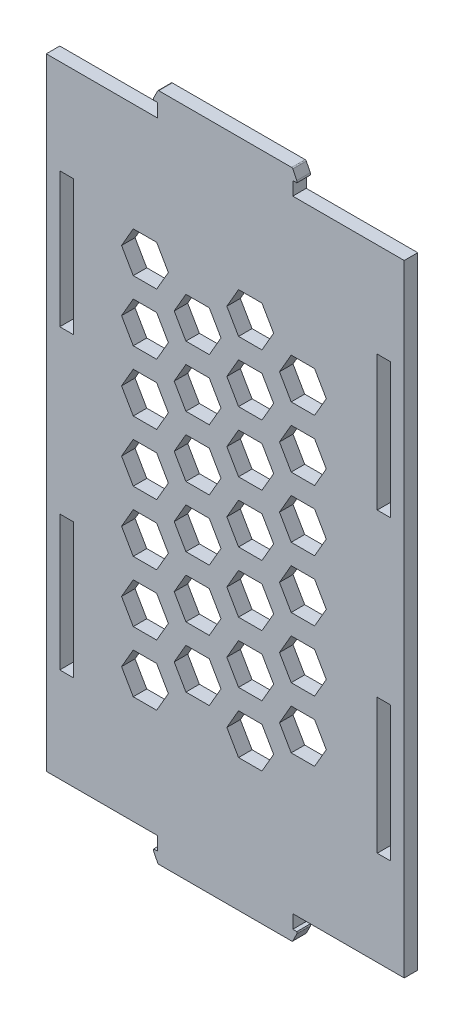
SolidWorks part; units mm, degrees
ref_plane "Front Plane" through (0, 0, 0) normal (0, 0, 1) x (1, 0, 0)
ref_plane "Top Plane" through (0, 0, 0) normal (0, 1, 0) x (1, 0, 0)
ref_plane "Right Plane" through (0, 0, 0) normal (1, 0, 0) x (0, 0, -1)
sketch "Sketch1" plane through (0, 0, 0) normal (0, 0, 1) x (1, 0, 0)
  line L0 (4, 0) -> (49, 0) construction
  line L1 (49, 0) -> (49, 92) construction
  line L2 (16.5, 0) -> (0, 0)
  line L3 (4, 92) -> (4, 0) construction
  line L8 (4, 46) -> (49, 46) construction
  line L30 (36.5, 0) -> (53, 0)
  line L44 (26.5, 68.0905) -> (26.5, 23.9095) construction
  line L45 (4, 78) -> (2, 78)
  line L46 (4, 78) -> (4, 58)
  line L47 (4, 58) -> (2, 58)
  line L48 (2, 78) -> (2, 58)
  line L49 (49, 78) -> (51, 78)
  line L50 (49, 78) -> (49, 58)
  line L51 (49, 58) -> (51, 58)
  line L52 (51, 78) -> (51, 58)
  line L69 (53, 0) -> (53, 92)
  line L77 (53, 92) -> (36.5, 92)
  line L99 (16.5, 92) -> (0, 92)
  line L100 (49, 14) -> (51, 14)
  line L101 (0, 92) -> (0, 0)
  line L102 (51, 14) -> (51, 34)
  line L103 (49, 34) -> (51, 34)
  line L104 (49, 14) -> (49, 34)
  line L105 (4, 14) -> (2, 14)
  line L106 (2, 14) -> (2, 34)
  line L107 (4, 34) -> (2, 34)
  line L108 (4, 14) -> (4, 34)
  line B0 (36.5, 0) -> (16.5, 0) construction
  line B1 (36.3382, -3.6) -> (16.6618, -3.6)
  line B2 (36.5, 0) -> (36.5, -2)
  line B3 (36.5, -3.5) -> (16.5, -3.5) construction
  line B4 (26.5, -3.5) -> (26.5, 0) construction
  line B5 (16.5, 0) -> (16.5, -2)
  line B6 (15.9, -2.3) -> (16.5, -3.5)
  line B7 (37.1, -2.3) -> (36.5, -3.5)
  line B8 (36.5, -2) -> (37.1, -2)
  line B9 (16.5, -2) -> (15.9, -2)
  arc B10 (36.5, -2) -> (37.1, -2.3) centre (36.8, -2.15) cw construction
  arc B11 (36.5, -3.5) -> (36.3382, -3.6) centre (36.3382, -3.4191) cw
  arc B12 (16.5, -3.5) -> (16.6618, -3.6) centre (16.6618, -3.4191) ccw
  arc B13 (37.1, -2) -> (37.1, -2.3) centre (36.8, -2.15) cw
  arc B14 (15.9, -2) -> (15.9, -2.3) centre (16.2, -2.15) ccw
  line B15 (36.5, 92) -> (16.5, 92) construction
  line B16 (36.3382, 95.6) -> (16.6618, 95.6)
  line B17 (36.5, 92) -> (36.5, 94)
  line B18 (36.5, 95.5) -> (16.5, 95.5) construction
  line B19 (26.5, 95.5) -> (26.5, 92) construction
  line B20 (16.5, 92) -> (16.5, 94)
  line B21 (15.9, 94.3) -> (16.5, 95.5)
  line B22 (37.1, 94.3) -> (36.5, 95.5)
  line B23 (36.5, 94) -> (37.1, 94)
  line B24 (16.5, 94) -> (15.9, 94)
  arc B25 (36.5, 94) -> (37.1, 94.3) centre (36.8, 94.15) ccw construction
  arc B26 (36.5, 95.5) -> (36.3382, 95.6) centre (36.3382, 95.4191) ccw
  arc B27 (16.5, 95.5) -> (16.6618, 95.6) centre (16.6618, 95.4191) cw
  arc B28 (37.1, 94) -> (37.1, 94.3) centre (36.8, 94.15) ccw
  arc B29 (15.9, 94) -> (15.9, 94.3) centre (16.2, 94.15) cw
  dimension "D3" = 12
  dimension "D4" = 2
  dimension "D16" = 92
  dimension "D17" = 20
  dimension "D18" = 2
  dimension "D20" = 22.5
sketch_block_instance "insert_bloquant_20mm-2mm-4"
sketch_block "insert_bloquant_20mm-2mm" parameters "D1"=2, "D2"=1.5, "D3"=1.2, "D4"=20, "D5"=0.1, "D6"=0.6
sketch_block_instance "insert_bloquant_20mm-2mm-5"
extrude "Boss-Extrude1" add sketch "Sketch1" along normal blind 2
sketch "Sketch2" plane through (0, 0, 2) normal (0, 0, 1) x (1, 0, 0)
  line L110 (53, 0) -> (53, 92) construction
  line L111 (0, 46) -> (53, 46) construction
  line L112 (0, 92) -> (0, 0) construction
  line B0 (16.3444, 16) -> (18.0765, 19)
  line B1 (18.0765, 19) -> (16.3444, 22)
  line B2 (20.6745, 26.5) -> (18.9425, 23.5)
  line B3 (20.6745, 20.5) -> (24.1386, 20.5)
  line B4 (24.1386, 20.5) -> (25.8707, 23.5)
  line B5 (25.8707, 23.5) -> (24.1386, 26.5)
  line B6 (12.8803, 25) -> (16.3444, 25)
  line B7 (16.3444, 25) -> (18.0765, 28)
  line B8 (18.0765, 28) -> (16.3444, 31)
  line B9 (20.6745, 35.5) -> (18.9425, 32.5)
  line B10 (20.6745, 29.5) -> (24.1386, 29.5)
  line B11 (24.1386, 29.5) -> (25.8707, 32.5)
  line B12 (25.8707, 32.5) -> (24.1386, 35.5)
  line B13 (12.8803, 40) -> (11.1483, 37)
  line B14 (12.8803, 34) -> (16.3444, 34)
  line B15 (16.3444, 34) -> (18.0765, 37)
  line B16 (18.0765, 37) -> (16.3444, 40)
  line B17 (20.6745, 44.5) -> (18.9425, 41.5)
  line B18 (20.6745, 38.5) -> (24.1386, 38.5)
  line B19 (24.1386, 38.5) -> (25.8707, 41.5)
  line B20 (25.8707, 41.5) -> (24.1386, 44.5)
  line B21 (12.8803, 49) -> (11.1483, 46)
  line B22 (12.8803, 52) -> (16.3444, 52)
  line B23 (11.1483, 19) -> (12.8803, 16)
  line B24 (12.8803, 43) -> (16.3444, 43)
  line B25 (16.3444, 43) -> (18.0765, 46)
  line B26 (18.0765, 46) -> (16.3444, 49)
  line B27 (16.3444, 52) -> (18.0765, 55)
  line B28 (18.0765, 55) -> (16.3444, 58)
  line B29 (20.6745, 62.5) -> (18.9425, 59.5)
  line B30 (20.6745, 56.5) -> (24.1386, 56.5)
  line B31 (24.1386, 56.5) -> (25.8707, 59.5)
  line B32 (25.8707, 59.5) -> (24.1386, 62.5)
  line B33 (12.8803, 67) -> (11.1483, 64)
  line B34 (12.8803, 61) -> (16.3444, 61)
  line B35 (16.3444, 61) -> (18.0765, 64)
  line B36 (18.0765, 64) -> (16.3444, 67)
  line B37 (20.6745, 71.5) -> (18.9425, 68.5)
  line B38 (20.6745, 65.5) -> (24.1386, 65.5)
  line B39 (24.1386, 65.5) -> (25.8707, 68.5)
  line B40 (25.8707, 68.5) -> (24.1386, 71.5)
  line B41 (12.8803, 76) -> (11.1483, 73)
  line B42 (12.8803, 70) -> (16.3444, 70)
  line B43 (16.3444, 70) -> (18.0765, 73)
  line B44 (18.0765, 73) -> (16.3444, 76)
  line B45 (24.1386, 47.5) -> (25.8707, 50.5)
  line B46 (25.8707, 50.5) -> (24.1386, 53.5)
  line B47 (12.8803, 22) -> (11.1483, 19)
  line B48 (12.8803, 16) -> (16.3444, 16)
  line B49 (16.3444, 22) -> (12.8803, 22)
  line B50 (18.9425, 23.5) -> (20.6745, 20.5)
  line B51 (24.1386, 26.5) -> (20.6745, 26.5)
  line B52 (16.3444, 67) -> (12.8803, 67)
  line B53 (11.1483, 64) -> (12.8803, 61)
  line B54 (16.3444, 49) -> (12.8803, 49)
  line B55 (11.1483, 46) -> (12.8803, 43)
  line B56 (16.3444, 31) -> (12.8803, 31)
  line B57 (12.8803, 31) -> (11.1483, 28)
  line B58 (11.1483, 28) -> (12.8803, 25)
  line B59 (24.1386, 35.5) -> (20.6745, 35.5)
  line B60 (18.9425, 32.5) -> (20.6745, 29.5)
  line B61 (11.1483, 73) -> (12.8803, 70)
  line B62 (16.3444, 76) -> (12.8803, 76)
  line B63 (18.9425, 68.5) -> (20.6745, 65.5)
  line B64 (24.1386, 71.5) -> (20.6745, 71.5)
  line B65 (11.1483, 55) -> (12.8803, 52)
  line B66 (12.8803, 58) -> (11.1483, 55)
  line B67 (16.3444, 58) -> (12.8803, 58)
  line B68 (18.9425, 59.5) -> (20.6745, 56.5)
  line B69 (24.1386, 62.5) -> (20.6745, 62.5)
  line B70 (18.9425, 50.5) -> (20.6745, 47.5)
  line B71 (20.6745, 53.5) -> (18.9425, 50.5)
  line B72 (24.1386, 53.5) -> (20.6745, 53.5)
  line B73 (20.6745, 47.5) -> (24.1386, 47.5)
  line B74 (11.1483, 37) -> (12.8803, 34)
  line B75 (16.3444, 40) -> (12.8803, 40)
  line B76 (18.9425, 41.5) -> (20.6745, 38.5)
  line B77 (24.1386, 44.5) -> (20.6745, 44.5)
  line B78 (31.9329, 16) -> (33.6649, 19)
  line B79 (33.6649, 19) -> (31.9329, 22)
  line B80 (36.263, 26.5) -> (34.531, 23.5)
  line B81 (36.263, 20.5) -> (39.7271, 20.5)
  line B82 (39.7271, 20.5) -> (41.4592, 23.5)
  line B83 (41.4592, 23.5) -> (39.7271, 26.5)
  line B84 (28.4688, 25) -> (31.9329, 25)
  line B85 (31.9329, 25) -> (33.6649, 28)
  line B86 (33.6649, 28) -> (31.9329, 31)
  line B87 (36.263, 35.5) -> (34.531, 32.5)
  line B88 (36.263, 29.5) -> (39.7271, 29.5)
  line B89 (39.7271, 29.5) -> (41.4592, 32.5)
  line B90 (41.4592, 32.5) -> (39.7271, 35.5)
  line B91 (28.4688, 40) -> (26.7367, 37)
  line B92 (28.4688, 34) -> (31.9329, 34)
  line B93 (31.9329, 34) -> (33.6649, 37)
  line B94 (33.6649, 37) -> (31.9329, 40)
  line B95 (36.263, 44.5) -> (34.531, 41.5)
  line B96 (36.263, 38.5) -> (39.7271, 38.5)
  line B97 (39.7271, 38.5) -> (41.4592, 41.5)
  line B98 (41.4592, 41.5) -> (39.7271, 44.5)
  line B99 (28.4688, 49) -> (26.7367, 46)
  line B100 (28.4688, 52) -> (31.9329, 52)
  line B101 (26.7367, 19) -> (28.4688, 16)
  line B102 (28.4688, 43) -> (31.9329, 43)
  line B103 (31.9329, 43) -> (33.6649, 46)
  line B104 (33.6649, 46) -> (31.9329, 49)
  line B105 (31.9329, 52) -> (33.6649, 55)
  line B106 (33.6649, 55) -> (31.9329, 58)
  line B107 (36.263, 62.5) -> (34.531, 59.5)
  line B108 (36.263, 56.5) -> (39.7271, 56.5)
  line B109 (39.7271, 56.5) -> (41.4592, 59.5)
  line B110 (41.4592, 59.5) -> (39.7271, 62.5)
  line B111 (28.4688, 67) -> (26.7367, 64)
  line B112 (28.4688, 61) -> (31.9329, 61)
  line B113 (31.9329, 61) -> (33.6649, 64)
  line B114 (33.6649, 64) -> (31.9329, 67)
  line B115 (36.263, 71.5) -> (34.531, 68.5)
  line B116 (36.263, 65.5) -> (39.7271, 65.5)
  line B117 (39.7271, 65.5) -> (41.4592, 68.5)
  line B118 (41.4592, 68.5) -> (39.7271, 71.5)
  line B119 (28.4688, 76) -> (26.7367, 73)
  line B120 (28.4688, 70) -> (31.9329, 70)
  line B121 (31.9329, 70) -> (33.6649, 73)
  line B122 (33.6649, 73) -> (31.9329, 76)
  line B123 (39.7271, 47.5) -> (41.4592, 50.5)
  line B124 (41.4592, 50.5) -> (39.7271, 53.5)
  line B125 (28.4688, 22) -> (26.7367, 19)
  line B126 (28.4688, 16) -> (31.9329, 16)
  line B127 (31.9329, 22) -> (28.4688, 22)
  line B128 (34.531, 23.5) -> (36.263, 20.5)
  line B129 (39.7271, 26.5) -> (36.263, 26.5)
  line B130 (31.9329, 67) -> (28.4688, 67)
  line B131 (26.7367, 64) -> (28.4688, 61)
  line B132 (31.9329, 49) -> (28.4688, 49)
  line B133 (26.7367, 46) -> (28.4688, 43)
  line B134 (30.2008, 19) -> (30.2008, 76) construction
  line B135 (31.9329, 31) -> (28.4688, 31)
  line B136 (28.4688, 31) -> (26.7367, 28)
  line B137 (26.7367, 28) -> (28.4688, 25)
  line B138 (39.7271, 35.5) -> (36.263, 35.5)
  line B139 (34.531, 32.5) -> (36.263, 29.5)
  line B140 (26.7367, 73) -> (28.4688, 70)
  line B141 (31.9329, 76) -> (28.4688, 76)
  line B142 (34.531, 68.5) -> (36.263, 65.5)
  line B143 (39.7271, 71.5) -> (36.263, 71.5)
  line B144 (26.7367, 55) -> (28.4688, 52)
  line B145 (28.4688, 58) -> (26.7367, 55)
  line B146 (31.9329, 58) -> (28.4688, 58)
  line B147 (34.531, 59.5) -> (36.263, 56.5)
  line B148 (39.7271, 62.5) -> (36.263, 62.5)
  line B149 (34.531, 50.5) -> (36.263, 47.5)
  line B150 (36.263, 53.5) -> (34.531, 50.5)
  line B151 (39.7271, 53.5) -> (36.263, 53.5)
  line B152 (36.263, 47.5) -> (39.7271, 47.5)
  line B153 (26.7367, 37) -> (28.4688, 34)
  line B154 (31.9329, 40) -> (28.4688, 40)
  line B155 (34.531, 41.5) -> (36.263, 38.5)
  line B156 (39.7271, 44.5) -> (36.263, 44.5)
sketch_block_instance "Alveole_12mm_4mm_8x2-6"
sketch_block "Alveole_12mm_4mm_8x2" parameters "D1"=7, "D2"=1.5, "D3"=13.2857, "D4"=14
sketch_block_instance "Alveole_12mm_4mm_8x2-7"
extrude "Cut-Extrude1" cut sketch "Sketch2" against normal through all
